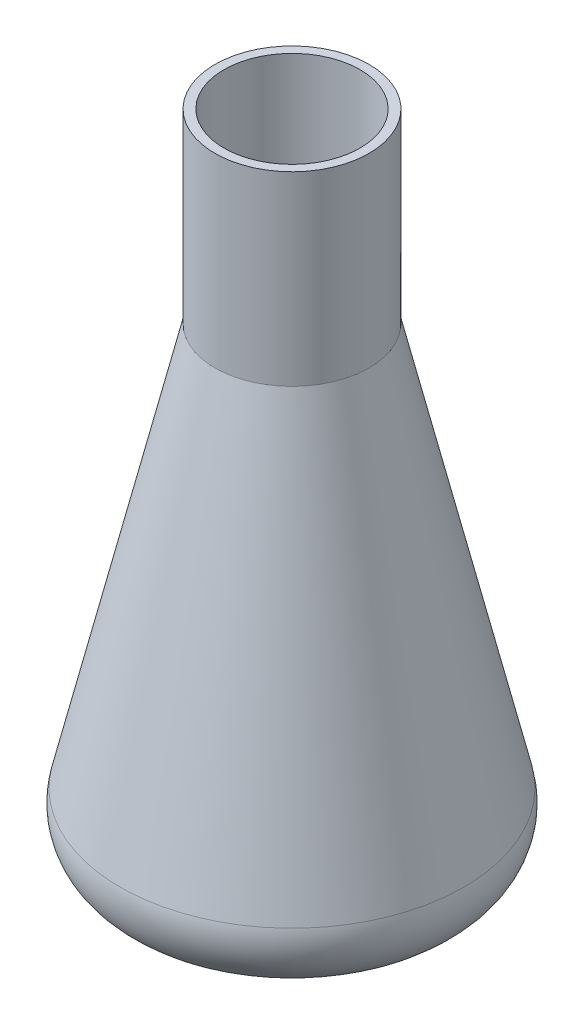
SolidWorks part; units mm, degrees
ref_plane "Alzado" through (0, 0, 0) normal (0, 0, 1) x (1, 0, 0)
ref_plane "Planta" through (0, 0, 0) normal (0, 1, 0) x (1, 0, 0)
ref_plane "Vista lateral" through (0, 0, 0) normal (1, 0, 0) x (0, 0, -1)
sketch "Croquis2" plane through (0, 0, 0) normal (0, 0, 1) x (1, 0, 0)
  line L0 (0, 0) -> (0, 145) construction
  line L1 (0, 145) -> (17, 145) construction
  line L2 (17, 145) -> (17, 104)
  line L3 (0, 0) -> (25.7932, 0)
  line L4 (37.8984, 15.2883) -> (17, 104)
  line L5 (17, 145) -> (15, 145)
  line L6 (15, 145) -> (15, 103.7676)
  line L7 (15, 103.7676) -> (35.5922, 16.356)
  line L8 (24.2252, 2) -> (0, 2)
  line L9 (0, 2) -> (0, 0)
  arc A0 (35.5922, 16.356) -> (24.2252, 2) centre (24.2252, 13.6782) cw
  arc A1 (37.8984, 15.2883) -> (25.7932, 0) centre (25.7932, 12.4366) cw
  point P14 (41.5, 0)
  dimension "D6" = 2
  dimension "D7" = 41
  dimension "D1" = 17
  dimension "D2" = 41.5
  dimension "D3" = 2
  dimension "D4" = 2
  dimension "D5" = 2
  dimension "D8" = 145
revolve "Revolución1" add sketch "Croquis2" angle 360 about L0
